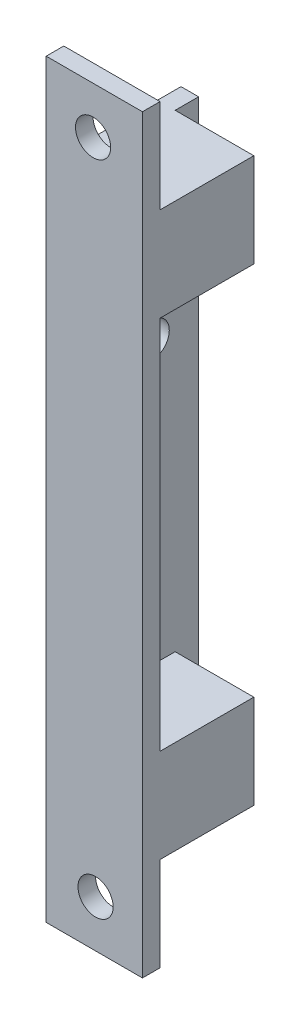
SolidWorks part; units mm, degrees
ref_plane "Front Plane" through (0, 0, 0) normal (0, 0, 1) x (1, 0, 0)
ref_plane "Top Plane" through (0, 0, 0) normal (0, 1, 0) x (1, 0, 0)
ref_plane "Right Plane" through (0, 0, 0) normal (1, 0, 0) x (0, 0, -1)
sketch "Sketch2" plane through (0, 0, 0) normal (1, 0, 0) x (0, 0, -1)
  line L1 (0, 0) -> (31.75, 0)
  line L2 (0, 0) -> (0, 152.4)
  line L3 (0, 152.4) -> (31.75, 152.4)
  line L4 (31.75, 0) -> (31.75, 152.4)
  circle A0 centre (19.05, 101.6) radius 4.7625
  dimension "D3" = 9.525
  dimension "D1" = 31.75
  dimension "D2" = 152.4
  dimension "D4" = 50.8
  dimension "D5" = 19.05
extrude "Boss-Extrude1" add sketch "Sketch2" against normal blind 4.7625
sketch "Sketch3" plane through (0, 0, 0) normal (0, 0, 1) x (1, 0, 0)
  line L0 (-4.7625, 152.4) -> (0, 152.4) construction
  line L1 (-4.7625, -25.4) -> (21.3079, -25.4)
  line L2 (-4.7625, -25.4) -> (-4.7625, 177.8)
  line L3 (-4.7625, 177.8) -> (21.3079, 177.8)
  line L4 (21.3079, -25.4) -> (21.3079, 177.8)
  circle A0 centre (7.9375, 165.1) radius 4.7625
  circle A1 centre (8.6079, -12.7) radius 4.7625
  point P6 (-2.3813, 152.4)
  dimension "D4" = 12.7
  dimension "D5" = 9.525
  dimension "D6" = 9.525
  dimension "D1" = 25.4
  dimension "D2" = 203.2
  dimension "D3" = 12.7
  dimension "D7" = 12.7
  dimension "D8" = 12.7
extrude "Boss-Extrude2" add sketch "Sketch3" along normal blind 4.7625
sketch "Sketch4" plane through (0, 0, 0) normal (0, 0, -1) x (-1, 0, 0)
  line L0 (-21.3079, -25.4) -> (-21.3079, 177.8) construction
  line L1 (0, 152.4) -> (-21.3079, 152.4)
  line L2 (0, 152.4) -> (0, 127)
  line L3 (0, 127) -> (-21.3079, 127)
  line L4 (-21.3079, 152.4) -> (-21.3079, 127)
  line L6 (0, 0) -> (-21.3079, 0)
  line L7 (0, 0) -> (0, 25.4)
  line L8 (0, 25.4) -> (-21.3079, 25.4)
  line L9 (-21.3079, 0) -> (-21.3079, 25.4)
  dimension "D1" = 25.4
  dimension "D2" = 25.4
extrude "Boss-Extrude3" add sketch "Sketch4" along normal blind 25.4 contours L3 L4 L1 L2 | L6 L9 L8 L7
